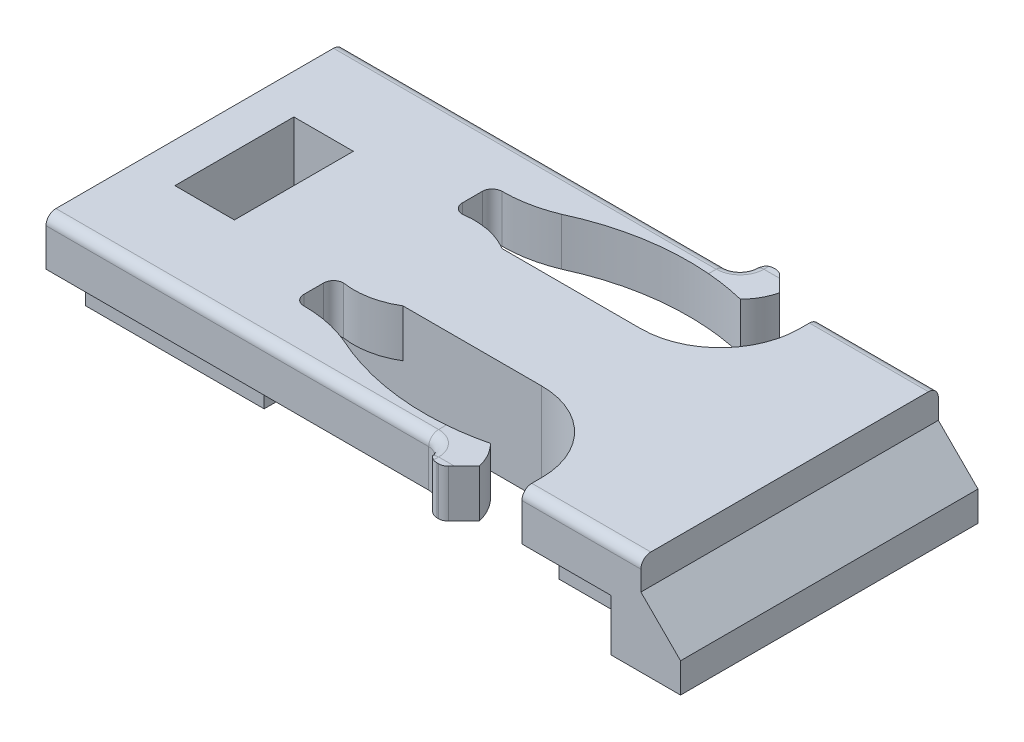
SolidWorks part; units mm, degrees
ref_plane "前视基准面" through (0, 0, 0) normal (0, 0, 1) x (1, 0, 0)
ref_plane "上视基准面" through (0, 0, 0) normal (0, 1, 0) x (1, 0, 0)
ref_plane "右视基准面" through (0, 0, 0) normal (1, 0, 0) x (0, 0, -1)
other "Configuration Table"
sketch "草图1" plane through (0, 0, 0) normal (0, 1, 0) x (1, 0, 0)
  line L1 (0, 0) -> (35, 0)
  line L2 (0, 0) -> (0, 15)
  line L3 (0, 15) -> (35, 15)
  line L4 (35, 0) -> (35, 15)
  dimension "D1" = 15
  dimension "D2" = 35
extrude "凸台-拉伸1" add sketch "草图1" along normal blind 2.4
fillet "圆角1" radius 0.5 2 edges at (17.5, 2.4, -15) (17.5, 2.4, 0)
sketch "草图2" plane through (0, 0, 0) normal (0, -1, 0) x (1, 0, 0)
  line L0 (0, -15) -> (0, 0) construction
  line L1 (0, -2) -> (35, -2)
  line L2 (0, -2) -> (0, -13)
  line L3 (0, -13) -> (35, -13)
  line L4 (35, -2) -> (35, -13)
  line L5 (35, 0) -> (35, -15) construction
  line L7 (35, -15) -> (0, -15) construction
  dimension "D1" = 11
  dimension "D2" = 2
extrude "凸台-拉伸2" add sketch "草图2" along normal blind 2.6
sketch "草图3" plane through (0, 0, 0) normal (0, -1, 0) x (1, 0, 0)
  line L0 (0, 0) -> (35, 0) construction
  line L1 (35, -2) -> (31.5, -2)
  line L2 (35, -2) -> (35, 0)
  line L3 (35, 0) -> (31.5, 0)
  line L4 (31.5, -2) -> (31.5, 0)
  dimension "D1" = 3.5
extrude "凸台-拉伸3" add sketch "草图3" along normal blind 2.6
ref_plane "基准面1" through (0, 0, -7.5) normal (0, 0, -1) x (-1, 0, 0)
mirror "镜向1" about plane through (0, 0, -7.5) normal (0, 0, -1) of "凸台-拉伸3"
sketch "草图4" plane through (0, 0, -15) normal (0, 0, -1) x (-1, 0, 0)
  line L0 (-35, -1.1) -> (-33, 0.9)
  line L1 (-35, 1.9) -> (-35, -2.6) construction
  line L2 (-33, 0.9) -> (-33, 2.4)
  line L3 (-35, 2.4) -> (0, 2.4) construction
  line L4 (-33, 2.4) -> (-35, 2.4)
  line L5 (-35, 2.4) -> (-35, -1.1)
  dimension "D1" = 1.5
  dimension "D2" = 2
  dimension "D3" = 45
extrude "切除-拉伸1" cut sketch "草图4" against normal blind 15
sketch "草图6" plane through (0, 2.4, 0) normal (0, 1, 0) x (1, 0, 0)
  line L0 (0, 15) -> (33, 15) construction
  line L1 (12, 15) -> (27, 15)
  line L2 (12, 15) -> (12, 10)
  line L3 (12, 10) -> (23, 10)
  line L4 (27, 15) -> (27, 14)
  line L6 (35, 0) -> (35, 15) construction
  arc A0 (23, 10) -> (27, 14) centre (23, 14) ccw
  dimension "D4" = 4
  dimension "D1" = 5
  dimension "D2" = 8
  dimension "D3" = 15
extrude "切除-拉伸2" cut sketch "草图6" against normal blind 5
ref_plane "基准面2" through (0, 0, -16) normal (0, 0, -1) x (-1, 0, 0)
sketch "草图10" plane through (0, 0, -16) normal (0, 0, -1) x (-1, 0, 0)
  line L0 (-12, 2.4) -> (-23, 2.4) construction
  line L1 (-25, 2.4) -> (-23.5, 2.4)
  line L2 (-25, 2.4) -> (-25, 0)
  line L3 (-25, 0) -> (-23, 0)
  line L4 (-23, 1.9) -> (-23, 0)
  line L5 (-27, 0) -> (-27, 1.9) construction
  arc A0 (-23.5, 2.4) -> (-23, 1.9) centre (-23.5, 1.9) cw
  point P8 (0, 0)
  point P9 (0, 0)
  point P12 (-23, 2.4)
  dimension "D4" = 0.5
  dimension "D1" = 2.4
  dimension "D2" = 2
  dimension "D3" = 2
sketch "草图13" plane through (0, 2.4, 0) normal (0, 1, 0) x (1, 0, 0)
  line L0 (12, 14.5) -> (22.3, 14.5)
  line L1 (23.5, 15.7) -> (23.5, 16)
  arc A0 (22.3, 14.5) -> (23.5, 15.7) centre (22.3, 15.7) ccw
  dimension "D1" = 1.2
sweep "扫描4" add profiles "草图10" path "草图13"
sketch "草图14" plane through (0, 0, 0) normal (0, -1, 0) x (1, 0, 0)
  line L0 (22.7215, -16) -> (22.7215, -15.2215)
  line L1 (22.7215, -15.2215) -> (23.5, -16)
  line L2 (25, -16) -> (23, -16) construction
  line L3 (23.5, -16) -> (22.7215, -16)
  line L4 (25.1094, -16) -> (25.1094, -14.8906)
  line L6 (25.1094, -14.8906) -> (24, -16)
  line L7 (24, -16) -> (25.1094, -16)
  line L8 (23, -15.7) -> (23, -16) construction
  point P10 (23, -16.2039)
  point P11 (24.9919, -16.2621)
  point P12 (24.9966, -16.3451)
  point P15 (25, -16.5)
  point P17 (22.7838, -15.7595)
  point P18 (22.9123, -14.9821)
  point P19 (22.7215, -15.2215)
  point P20 (25.1277, -17.0377)
  point P22 (25.3866, -17.209)
  dimension "D1" = 0.5
  dimension "D2" = 45
  dimension "D5" = 0.5
  dimension "D6" = 45
extrude "切除-拉伸3" cut sketch "草图14" against normal blind 2.4
sketch "草图15" plane through (0, 0, 0) normal (0, -1, 0) x (1, 0, 0)
  line L0 (12, -10) -> (12, -13)
  line L2 (12, -13) -> (16, -13)
  line L3 (12, -13) -> (22.3, -13) construction
  line L6 (13, -12) -> (13, -11)
  line L9 (16, -10) -> (12, -10)
  arc A0 (13.5, -12.5) -> (13, -12) centre (13.5, -12) cw
  arc A1 (13, -11) -> (13.5, -10.5) centre (13.5, -11) cw
  arc A2 (13.5, -10.5) -> (16, -10) centre (14.0619, -6.8096) ccw
  arc A3 (16, -13) -> (13.5, -12.5) centre (13.5, -19) ccw
  point P18 (13, -12.5)
  point P21 (13, -10.5)
  dimension "D4" = 0.5
  dimension "D2" = 2
  dimension "D3" = 1
  dimension "D5" = 4
  dimension "D6" = 4
extrude "凸台-拉伸4" add sketch "草图15" against normal blind 2.4
sketch "草图16" plane through (0, 0, 0) normal (0, -1, 0) x (1, 0, 0)
  line L3 (16, -13) -> (22.3, -13)
  line L4 (16, -13) -> (22.3, -13)
  arc A0 (16, -13) -> (24.2171, -13.7987) centre (21.25, -1.6559) ccw
  arc A3 (24.9263, -15.0737) -> (22.3, -13) centre (22.3, -15.7) ccw
  arc A4 (24.2171, -13.7987) -> (22.3, -13) centre (22.3, -15.7) ccw
  dimension "D1" = 25
  dimension "D2" = 0
extrude "切除-拉伸4" cut sketch "草图16" against normal blind 2.4
fillet "圆角2" radius 0.5 2 edges at (23.5, 1.2, -16) (24, 1.2, -16)
ref_plane "基准面3" through (0, 0, -7.5) normal (0, 0, 1) x (1, 0, 0)
mirror "镜向2" about plane through (0, 0, -7.5) normal (0, 0, 1) of "圆角2", "切除-拉伸4", "凸台-拉伸4", "切除-拉伸3", "扫描4", "切除-拉伸2"
sketch "草图17" plane through (0, 0, -15) normal (0, 0, -1) x (-1, 0, 0)
  line L0 (-22.3, 2.4) -> (0, 2.4) construction
  line L1 (0, -2.6) -> (-3, -2.6)
  line L2 (0, -2.6) -> (0, 2.4)
  line L3 (0, 2.4) -> (-3, 2.4)
  line L4 (-3, -2.6) -> (-3, 2.4)
  dimension "D1" = 3
extrude "切除-拉伸5" cut sketch "草图17" against normal blind 15
sketch "草图18" plane through (0, 2.4, 0) normal (0, 1, 0) x (1, 0, 0)
  line L0 (1.045, 7.5) -> (-1.045, 7.5) construction
  line L1 (5, 10.5) -> (8, 10.5)
  line L2 (5, 10.5) -> (5, 4.5)
  line L3 (5, 4.5) -> (8, 4.5)
  line L4 (8, 10.5) -> (8, 4.5)
  line L5 (3, 0.5) -> (3, 14.5) construction
  dimension "D1" = 6
  dimension "D2" = 3
  dimension "D3" = 3
  dimension "D4" = 2
extrude "切除-拉伸6" cut sketch "草图18" against normal blind 5
